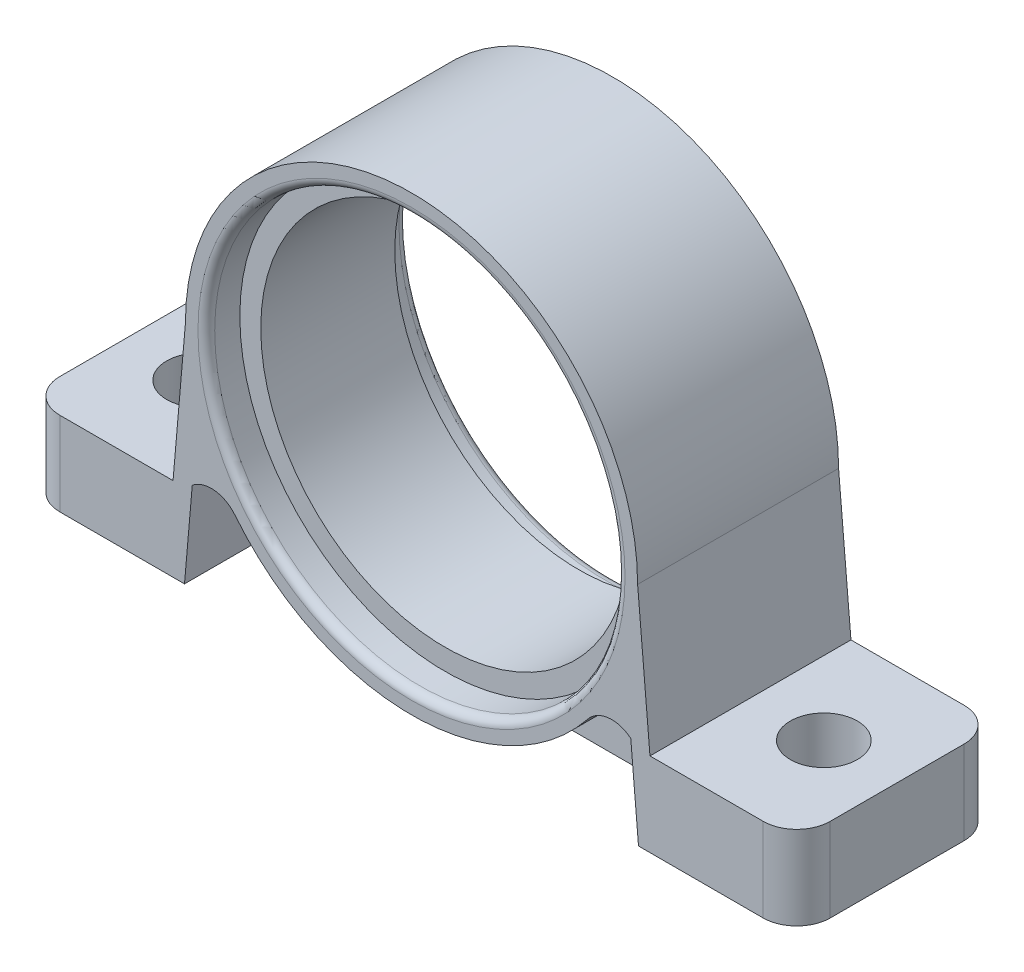
SolidWorks part; units mm, degrees
ref_plane "Alzado" through (0, 0, 0) normal (0, 0, 1) x (1, 0, 0)
ref_plane "Planta" through (0, 0, 0) normal (0, 1, 0) x (1, 0, 0)
ref_plane "Vista lateral" through (0, 0, 0) normal (1, 0, 0) x (0, 0, -1)
sketch "Croquis1" plane through (0, 0, 0) normal (0, 0, 1) x (1, 0, 0)
  line L0 (23, -13.5) -> (-23, -13.5)
  line L1 (0, 0) -> (0, -13.5) construction
  line L2 (-23, -13.5) -> (-23, -8.5)
  line L3 (-23, -8.5) -> (-14.2379, -8.5)
  line L4 (-13.5, 0) -> (-14.2379, -8.5)
  line L5 (23, -13.5) -> (23, -8.5)
  line L6 (23, -8.5) -> (14.2379, -8.5)
  line L7 (13.5, 0) -> (14.2379, -8.5)
  line L8 (0, 14.5) -> (4.972, 14.5) construction
  line L9 (0, 13.5) -> (4.972, 13.5) construction
  arc A0 (13.5, 0) -> (-13.5, 0) centre (0, 0) ccw
  circle A1 centre (0, 0) radius 11
  dimension "D1" = 14.5
  dimension "D2" = 13.5
  dimension "D4" = 13.5
  dimension "D3" = 5
  dimension "D5" = 1
  dimension "D6" = 27
extrude "Saliente-Extruir1" add sketch "Croquis1" along normal mid plane 12
sketch "Croquis2" plane through (0, -8.5, 0) normal (0, 1, 0) x (1, 0, 0)
  line L0 (-18.619, 6) -> (-18.619, -6) construction
  line L3 (-23, 0) -> (-14.2379, 0) construction
  line L4 (-23, -6) -> (-23, 6) construction
  line L5 (-14.2379, -6) -> (-14.2379, 6) construction
  line L6 (-14.2379, 6) -> (-23, 6) construction
  line L7 (-14.2379, -6) -> (-23, -6) construction
  line L8 (0, 6) -> (0, -6) construction
  line L9 (13.5, 6) -> (-13.5, 6) construction
  line L10 (-13.5, -6) -> (13.5, -6) construction
  circle A0 centre (-18.619, 0) radius 2
  circle A1 centre (18.619, 0) radius 2
extrude "Cortar-Extruir1" cut sketch "Croquis2" against normal through all
sketch "Croquis3" plane through (0, 0, 6) normal (0, 0, 1) x (1, 0, 0)
  line L0 (13.5539, -13.5) -> (14.0941, -17.3534)
  line L1 (13.0908, -8.1659) -> (13.5539, -13.5)
  line L2 (-23, -13.5) -> (23, -13.5) construction
  line L3 (14.0941, -17.3534) -> (-15.8739, -18.0452)
  line L4 (0, 0) -> (0, -8.4219) construction
  line L5 (-15.8739, -18.0452) -> (-13.5539, -13.5)
  line L6 (-13.0908, -8.1659) -> (-13.5539, -13.5)
  arc A0 (-10.5396, -8.4359) -> (10.5508, -8.4219) centre (0, 0) ccw
  arc A2 (-13.0908, -8.1659) -> (-10.5396, -8.4359) centre (-11.9489, -9.5639) cw
  arc A3 (13.0908, -8.1659) -> (10.5396, -8.4359) centre (11.9489, -9.5639) ccw
  line M5 (-23, -13.5) -> (23, -13.5)
extrude "Cortar-Extruir2" cut sketch "Croquis3" against normal through all contours L1 A3 A0 A2 L6 M5
sketch "Croquis5" plane through (0, 0, 0) normal (0, 0, 1) x (1, 0, 0)
  line L0 (-13.5539, -13.5) -> (13.5539, -13.5)
  line L1 (13.5539, -13.5) -> (13.0908, -8.1659)
  line L2 (13.0908, -8.1659) -> (11.0526, -6.7449)
  line L3 (11.0526, -6.7449) -> (3.3812, -12.2831)
  line L4 (3.3812, -12.2831) -> (-4.3576, -12.0666)
  line L5 (-4.3576, -12.0666) -> (-11.573, -6.7449)
  line L6 (-11.573, -6.7449) -> (-13.3223, -7.4554)
  line L7 (-13.3223, -7.4554) -> (-13.5539, -13.5)
extrude "Saliente-Extruir2" add sketch "Croquis5" along normal mid plane 4
sketch "Croquis6" plane through (0, 0, 6) normal (0, 0, 1) x (1, 0, 0)
  circle A0 centre (0, 0) radius 12.25
extrude "Cortar-Extruir3" cut sketch "Croquis6" against normal blind 2
sketch "Croquis7" plane through (0, 0, -6) normal (0, 0, -1) x (-1, 0, 0)
  circle A0 centre (0, 0) radius 12.25
extrude "Cortar-Extruir4" cut sketch "Croquis7" against normal blind 2
fillet "Redondeo1" radius 2 1 edges at (23, -11, -6)
fillet "Redondeo2" radius 2 1 edges at (23, -11, 6)
fillet "Redondeo3" radius 2 2 edges at (-23, -11, -6) (-23, -11, 6)
fillet "Redondeo4" radius 0.5 2 edges at (12.25, 0, 6) (-12.25, 0, -6)
